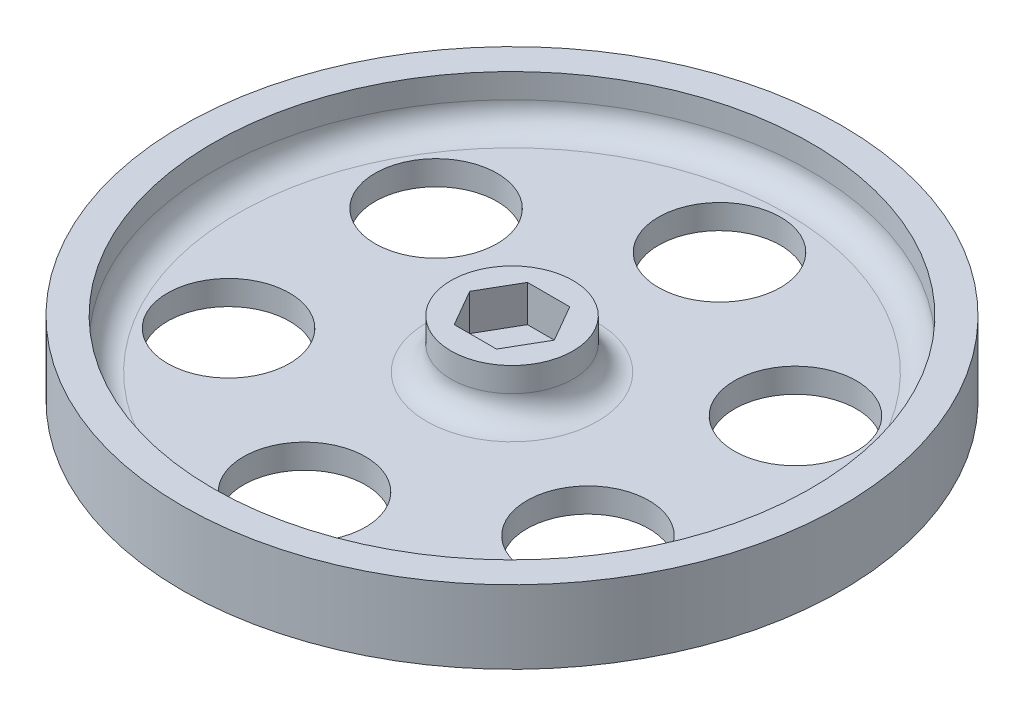
SolidWorks part; units mm, degrees
ref_plane "Front Plane" through (0, 0, 0) normal (0, 0, 1) x (1, 0, 0)
ref_plane "Top Plane" through (0, 0, 0) normal (0, 1, 0) x (1, 0, 0)
ref_plane "Right Plane" through (0, 0, 0) normal (1, 0, 0) x (0, 0, -1)
sketch "Sketch1" plane through (0, 0, 0) normal (0, 1, 0) x (1, 0, 0)
  circle A0 centre (0, 0) radius 54
  dimension "D1" = 108
extrude "Boss-Extrude1" add sketch "Sketch1" along normal mid plane 12
sketch "Sketch2" plane through (0, 6, 0) normal (0, 1, 0) x (1, 0, 0)
  circle A0 centre (0, 0) radius 49
  circle A1 centre (0, 0) radius 10
  dimension "D1" = 98
  dimension "D2" = 20
extrude "Cut-Extrude1" cut sketch "Sketch2" against normal blind 8
sketch "Sketch3" plane through (0, 6, 0) normal (0, 1, 0) x (1, 0, 0)
  line L1 (6.9282, 0) -> (3.4641, 6)
  line L2 (3.4641, 6) -> (-3.4641, 6)
  line L3 (-3.4641, 6) -> (-6.9282, 0)
  line L4 (-6.9282, 0) -> (-3.4641, -6)
  line L5 (-3.4641, -6) -> (3.4641, -6)
  line L6 (3.4641, -6) -> (6.9282, 0)
  circle A0 centre (0, 0) radius 6 construction
  point P1 (4.1709, -6)
  dimension "D1" = 12
extrude "Cut-Extrude2" cut sketch "Sketch3" against normal blind 6
sketch "Sketch4" plane through (0, 0, 0) normal (0, 1, 0) x (1, 0, 0)
  circle A0 centre (0, 0) radius 2
  dimension "D1" = 4
extrude "Cut-Extrude3" cut sketch "Sketch4" against normal up to surface (6 mm away) up to face at (0, -6, 54)
sketch "Sketch6" plane through (0, -2, 0) normal (0, 1, 0) x (1, 0, 0)
  circle A0 centre (0, 0) radius 34 construction
  circle A1 centre (0, 34) radius 10
  circle A2 centre (29.4449, 17) radius 10
  circle A3 centre (0, 0) radius 34 construction
  circle A4 centre (29.4449, -17) radius 10
  circle A5 centre (0, 0) radius 34 construction
  circle A6 centre (0, -34) radius 10
  circle A7 centre (0, 0) radius 34 construction
  circle A8 centre (-29.4449, -17) radius 10
  circle A9 centre (0, 0) radius 34 construction
  circle A10 centre (-29.4449, 17) radius 10
  circle A11 centre (0, 0) radius 34 construction
  point P5 (0, 0)
  point P23 (0, 0)
  dimension "D1" = 68
  dimension "D3" = 20
  dimension "D2" = 6
extrude "Cut-Extrude5" cut sketch "Sketch6" against normal up to surface (4 mm away) up to face at (0, -6, 2)
fillet "Fillet1" radius 4 2 edges at (0, -2, 10) (0, -2, 49)
